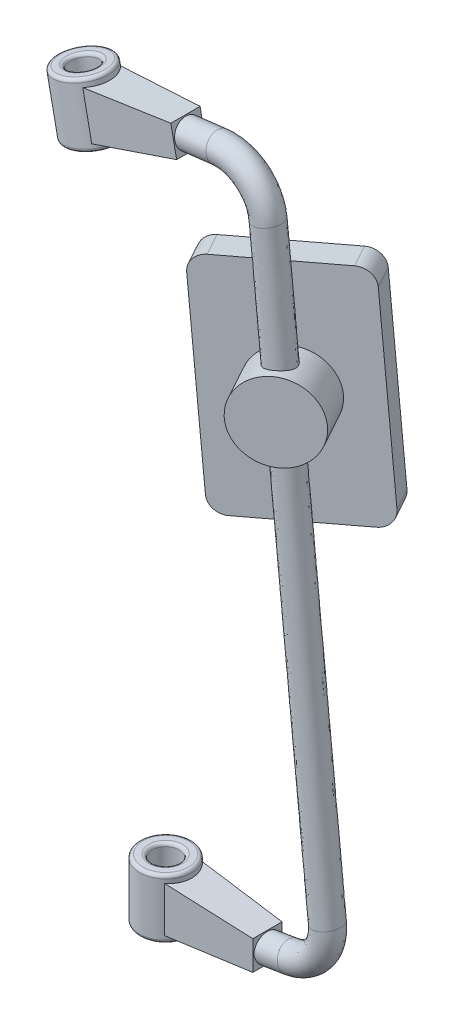
SolidWorks part; units mm, degrees
ref_plane "Front Plane" through (0, 0, 0) normal (0, 0, 1) x (1, 0, 0)
ref_plane "Top Plane" through (0, 0, 0) normal (0, 1, 0) x (1, 0, 0)
ref_plane "Right Plane" through (0, 0, 0) normal (1, 0, 0) x (0, 0, -1)
sketch "Sketch1" plane through (0, 0, 0) normal (0, 1, 0) x (1, 0, 0)
  circle A0 centre (0, 0) radius 12.5
  circle A1 centre (0, 0) radius 24
  dimension "D1" = 25
  dimension "D2" = 48
extrude "Boss-Extrude1" add sketch "Sketch1" along normal mid plane 55 contours A1 | A0
fillet "Fillet1" radius 3 4 edges at (0, 27.5, 12.5) (0, 27.5, 24) (0, -27.5, 12.5) (0, -27.5, 24)
ref_plane "Plane1" through (15, 0, 0) normal (1, 0, 0) x (0, 0, -1)
sketch "Sketch4" plane through (15, 0, 0) normal (1, 0, 0) x (0, 0, -1)
  line L0 (-20.6117, 0) -> (41.9806, 0) construction
  line L1 (0, 23.0094) -> (0, -24.2714) construction
  line L3 (-17.5, 21) -> (17.5, 21)
  line L4 (-17.5, 21) -> (-17.5, -21)
  line L5 (-17.5, -21) -> (17.5, -21)
  line L6 (17.5, 21) -> (17.5, -21)
  circle A0 centre (0, 0) radius 12.5
  dimension "D1" = 25
  dimension "D2" = 42
  dimension "D3" = 35
sketch "Sketch6" plane through (0, 0, 0) normal (0, 0, 1) x (1, 0, 0)
  line L0 (94, 0) -> (-270.3195, 0) construction
  line L1 (0, -79.4187) -> (0, 200.8809) construction
  line L2 (-40, -137.5526) -> (-40, 194) construction
  line L3 (-40, 194) -> (-114.1897, 559.2311) construction
  line L4 (-40, 194) -> (-40, 202.5264) construction
  line L6 (15.5, 27.5) -> (-15.5, 27.5) construction
  line L7 (-65.6804, 569.0848) -> (-65.6804, 254.5249) construction
  line L8 (-114.1897, 559.2311) -> (-65.6804, 569.0848) construction
  line L9 (24, -24.5) -> (24, 24.5) construction
  line L10 (-206.2715, 568.588) -> (20.964, 614.7466) construction
  line L11 (-65.6804, 569.0848) -> (-84.3739, 661.1117) construction
  dimension "D1" = 40
  dimension "D2" = 372.69
  dimension "D3" = 11.482
  dimension "D4" = 166.5
  dimension "D5" = 49.5
  dimension "D6" = 70
  dimension "D7" = 27.5
  dimension "D8" = 94
  dimension "D9" = 94
ref_plane "Plane2" through (-65.6804, 569.0848, 0) normal (-0.1991, 0.98, 0) x (0.98, 0.1991, 0)
sketch "Sketch8" plane through (-65.6804, 569.0848, 0) normal (-0.1991, 0.98, 0) x (0.98, 0.1991, 0)
  circle A0 centre (0, 0) radius 24
  circle A1 centre (0, 0) radius 12.5
  dimension "D1" = 25
  dimension "D2" = 48
extrude "Boss-Extrude2" add sketch "Sketch8" along normal blind 55 separate body
fillet "Fillet2" radius 3 4 edges at (-100.1487, 618.2065, 0) (-88.8788, 620.4957, 0) (-89.2001, 564.3072, 0) (-77.9302, 566.5965, 0)
ref_plane "Plane3" through (94, 0, 0) normal (1, 0, 0) x (0, 0, -1)
sketch "Sketch11" plane through (94, 0, 0) normal (1, 0, 0) x (0, 0, -1)
  line L0 (-26.258, 0) -> (32.0372, 0) construction
  line L1 (-13.5, 13.5) -> (13.5, 13.5)
  line L2 (-13.5, 13.5) -> (-13.5, -13.5)
  line L3 (-13.5, -13.5) -> (13.5, -13.5)
  line L4 (13.5, 13.5) -> (13.5, -13.5)
  line L5 (0, 21.6136) -> (0, -31.9549) construction
  line L6 (0, -137.5526) -> (0, 194) construction
  dimension "D1" = 27
  dimension "D2" = 27
loft "Loft1" add section "Sketch4" section "Sketch11"
ref_plane "Plane4" through (47.9402, 9.7381, 0) normal (0.98, 0.1991, 0) x (0, 0, -1)
ref_plane "Plane5" through (62.64, 12.7241, 0) normal (0.98, 0.1991, 0) x (0, 0, -1)
sketch "Sketch14" plane through (62.64, 12.7241, 0) normal (0.98, 0.1991, 0) x (0, 0, -1)
  line L0 (-40.0874, 598.2699) -> (54.1514, 598.2699) construction
  line L1 (0, 629.9205) -> (0, 567.8792) construction
  line L4 (24, 622.7699) -> (-24, 622.7699) construction
  line L5 (-24, 573.7699) -> (24, 573.7699) construction
  line L6 (-24, 622.7699) -> (-24, 573.7699) construction
  line L7 (24, 573.7699) -> (24, 622.7699) construction
  line L9 (-17.5, 619.2699) -> (17.5, 619.2699)
  line L10 (-17.5, 619.2699) -> (-17.5, 577.2699)
  line L11 (-17.5, 577.2699) -> (17.5, 577.2699)
  line L12 (17.5, 619.2699) -> (17.5, 577.2699)
  circle A0 centre (0, 598.2699) radius 12.5
  dimension "D1" = 25
  dimension "D2" = 42
  dimension "D3" = 35
ref_plane "Plane6" through (20.964, 614.7466, 0) normal (0.98, 0.1991, 0) x (0, 0, -1)
sketch "Sketch15" plane through (20.964, 614.7466, 0) normal (0.98, 0.1991, 0) x (0, 0, -1)
  line L1 (-13.5, 13.5) -> (13.5, 13.5)
  line L2 (-13.5, 13.5) -> (-13.5, -13.5)
  line L3 (-13.5, -13.5) -> (13.5, -13.5)
  line L4 (13.5, 13.5) -> (13.5, -13.5)
  line L5 (-40.0874, 0) -> (54.1514, 0) construction
  line L6 (0, 18.0247) -> (0, -17.7591) construction
  line L7 (0, -27.5) -> (0, 66.4063) construction
  dimension "D1" = 27
  dimension "D2" = 27
loft "Loft2" add section "Sketch14" section "Sketch15"
sketch "Sketch16" plane through (0, 0, 0) normal (0, 0, 1) x (1, 0, 0)
  line L0 (20.964, 614.7466) -> (50.0307, 618.2474)
  line L1 (94.6061, 582.6051) -> (149.3849, 47.1347)
  line L3 (116.018, 3.5834) -> (94, 0)
  arc A0 (50.0307, 618.2474) -> (94.6061, 582.6051) centre (54.8138, 578.5344) cw
  arc A1 (149.3849, 47.1347) -> (116.018, 3.5834) centre (109.5926, 43.0639) cw
  point P16 (90.4617, 623.1169)
  point P19 (153.2208, 9.6381)
  dimension "D3" = 40
  dimension "D1" = 70
  dimension "D2" = 60
sketch "Sketch17" plane through (140.0589, 28.4503, 0) normal (0.98, 0.1991, 0) x (0, 0, -1)
  circle A0 centre (0, 598.2699) radius 12.5
  dimension "D1" = 25
sweep "Sweep2" add profiles "Sketch17" path "Sketch16"
sketch "Sketch18" plane through (0, 0, 0) normal (0, 0, 1) x (1, 0, 0)
  line L0 (84.3257, 683.0971) -> (163.998, -95.7106) construction
  line L1 (161.6774, 49.4032) -> (106.8985, 584.8736) construction
  line L2 (82.3137, 580.3367) -> (137.0925, 44.8663) construction
ref_plane "Plane8" through (38.1524, 3.903, 66.4268) normal (0.4974, 0.0509, 0.866) x (0.1018, -0.9948, 0)
sketch "Sketch20" plane through (38.1524, 3.903, 66.4268) normal (0.4974, 0.0509, 0.866) x (0.1018, -0.9948, 0)
  line L0 (-670.9687, 132.8536) -> (111.9037, 132.8536) construction
  circle A0 centre (-426.664, 132.8536) radius 35
  dimension "D1" = 70
ref_plane "Plane7" through (15.7692, 1.6132, 27.4557) normal (0.4974, 0.0509, 0.866) x (0.1018, -0.9948, 0)
extrude "Boss-Extrude5" add sketch "Sketch20" along normal mid plane 40 contours A0
sketch "Sketch19" plane through (15.7692, 1.6132, 27.4557) normal (0.4974, 0.0509, 0.866) x (0.1018, -0.9948, 0)
  line L0 (-426.664, 132.8536) -> (-426.664, 343.4733) construction
  line L1 (-426.664, 343.4733) -> (-426.664, 640.0699) construction
  line L2 (0, 132.8536) -> (234.3011, 132.8536) construction
  line L4 (-511.664, 197.8536) -> (-341.664, 197.8536)
  line L5 (-526.664, 182.8536) -> (-526.664, 82.8536)
  line L6 (-511.664, 67.8536) -> (-341.664, 67.8536)
  line L7 (-326.664, 182.8536) -> (-326.664, 82.8536)
  line L8 (-670.9687, 132.8536) -> (111.9037, 132.8536) construction
  arc A0 (-526.664, 82.8536) -> (-511.664, 67.8536) centre (-511.664, 82.8536) ccw
  arc A1 (-341.664, 67.8536) -> (-326.664, 82.8536) centre (-341.664, 82.8536) ccw
  arc A2 (-341.664, 197.8536) -> (-326.664, 182.8536) centre (-341.664, 182.8536) cw
  arc A3 (-511.664, 197.8536) -> (-526.664, 182.8536) centre (-511.664, 182.8536) ccw
  point P14 (-326.664, 67.8536)
  point P17 (-326.664, 197.8536)
  point P20 (-526.664, 197.8536)
  dimension "D3" = 15
  dimension "D1" = 200
  dimension "D2" = 130
extrude "Boss-Extrude6" add sketch "Sketch19" along normal up to surface (25 mm away) up to face at (129.5906, 439.0431, -34.7522)
